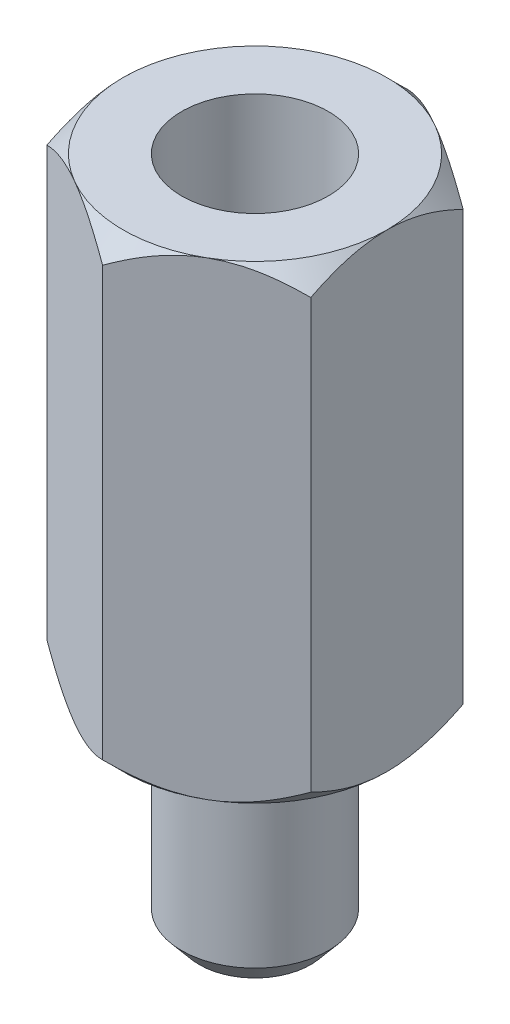
SolidWorks part; units mm, degrees
ref_plane "前视基准面" through (0, 0, 0) normal (0, 0, 1) x (1, 0, 0)
ref_plane "上视基准面" through (0, 0, 0) normal (0, 1, 0) x (1, 0, 0)
ref_plane "右视基准面" through (0, 0, 0) normal (1, 0, 0) x (0, 0, -1)
sketch "草图1" plane through (0, 0, 0) normal (0, 1, 0) x (1, 0, 0)
  circle A0 centre (0, 0) radius 1.25
  dimension "D1" = 2.5
extrude "凸台-拉伸1" add sketch "草图1" along normal blind 3.5
sketch "草图2" plane through (0, 3.5, 0) normal (0, 1, 0) x (1, 0, 0)
  line L1 (-2.25, 1.299) -> (-2.25, -1.299)
  line L2 (-2.25, -1.299) -> (0, -2.5981)
  line L3 (0, -2.5981) -> (2.25, -1.299)
  line L4 (2.25, -1.299) -> (2.25, 1.299)
  line L5 (2.25, 1.299) -> (0, 2.5981)
  line L6 (0, 2.5981) -> (-2.25, 1.299)
  circle A0 centre (0, 0) radius 2.25 construction
  dimension "D1" = 4.5
extrude "凸台-拉伸2" add sketch "草图2" along normal blind 8
sketch "草图3" plane through (0, 11.5, 0) normal (0, 1, 0) x (1, 0, 0)
  circle A0 centre (0, 0) radius 1.25
  dimension "D1" = 2.5
extrude "切除-拉伸1" cut sketch "草图3" against normal blind 4.8
sketch "草图5" plane through (0, 11.5, 0) normal (0, 1, 0) x (1, 0, 0)
  circle A0 centre (0, 0) radius 2.25
extrude "切除-拉伸2" cut sketch "草图5" against normal through all draft 45 flip side to cut
sketch "草图7" plane through (0, 3.5, 0) normal (0, -1, 0) x (1, 0, 0)
  circle A0 centre (0, 0) radius 2.25
extrude "切除-拉伸3" cut sketch "草图7" against normal through all draft 45 flip side to cut
chamfer "倒角1" distance 0.3 angle 50 1 edges at (0, 0, 1.25)
